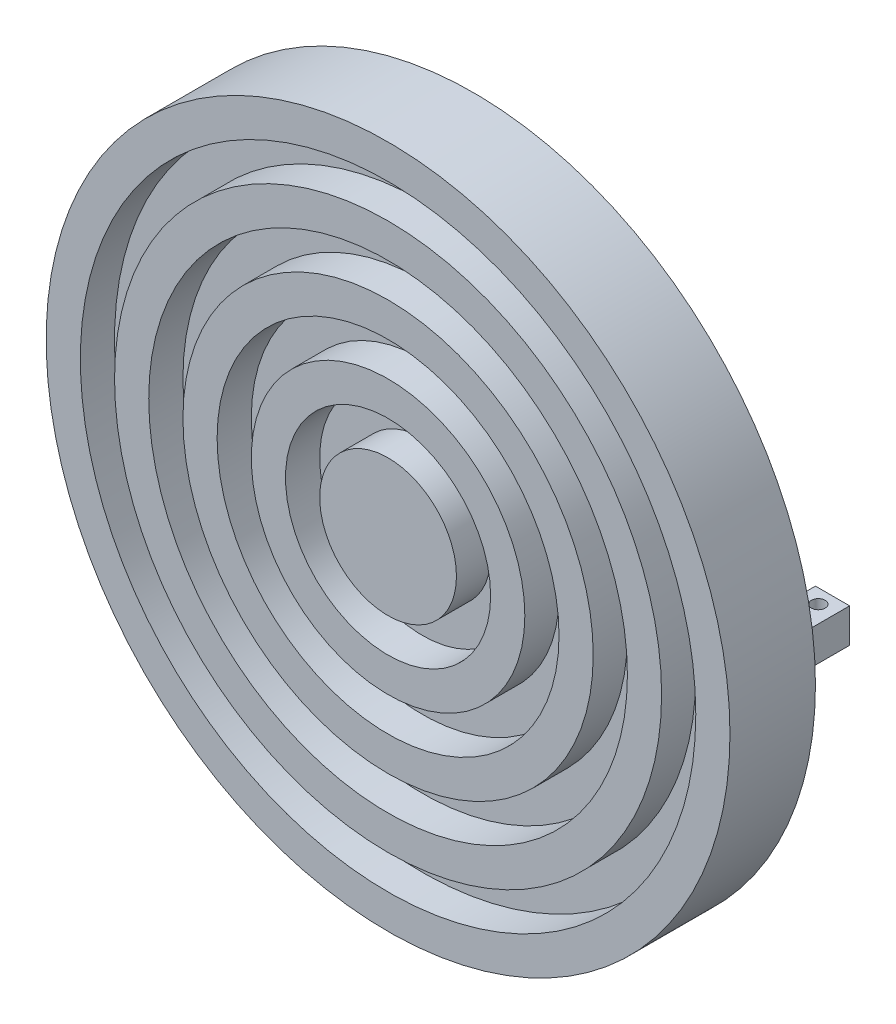
SolidWorks part; units mm, degrees
ref_plane "Front Plane" through (0, 0, 0) normal (1, 0, 0) x (0, 1, 0)
ref_plane "Top Plane" through (0, 0, 0) normal (0, 0, 1) x (0, 1, 0)
ref_plane "Right Plane" through (0, 0, 0) normal (0, 1, 0) x (-1, 0, 0)
sketch "Sketch1" plane through (0, 0, 0) normal (0, 0, 1) x (0, 1, 0)
  circle A0 centre (0, 0) radius 10
  dimension "D1" = 20
extrude "Boss-Extrude1" add sketch "Sketch1" along normal blind 2.5 contours A0
sketch "Sketch5" plane through (0, 0, 0) normal (0, 1, 0) x (-1, 0, 0)
  line L0 (0, 2.5) -> (0, -4.1897) construction
  line L1 (10, 2.5) -> (-10, 2.5) construction
  line L2 (-4, 2.5) -> (-4, 1.5)
  line L3 (-2, 2.5) -> (-3, 2.5)
  line L4 (-2, 2.5) -> (-2, 1.5)
  line L5 (-2, 1.5) -> (-3, 1.5)
  line L6 (-3, 2.5) -> (-3, 1.5)
  line L7 (-4, 2.5) -> (-5, 2.5)
  line L8 (-5, 2.5) -> (-5, 1.5)
  line L9 (-4, 1.5) -> (-5, 1.5)
  line L10 (-6, 2.5) -> (-6, 1.5)
  line L11 (-6, 2.5) -> (-7, 2.5)
  line L12 (-7, 2.5) -> (-7, 1.5)
  line L13 (-6, 1.5) -> (-7, 1.5)
  line L14 (-8, 2.5) -> (-8, 1.5)
  line L15 (-8, 2.5) -> (-9, 2.5)
  line L16 (-9, 2.5) -> (-9, 1.5)
  line L17 (-8, 1.5) -> (-9, 1.5)
  dimension "D1" = 2
  dimension "D2" = 3
  dimension "D3" = 1
  dimension "D4" = 4
revolve "Cut-Revolve1" cut sketch "Sketch5" angle 360 about L0
sketch "Sketch6" plane through (0, 0, 0) normal (0, 1, 0) x (-1, 0, 0)
  line L0 (0, -0.1135) -> (0, -3.7394) construction
  line L1 (-10, 0) -> (10, 0) construction
  line L2 (-2, 0) -> (-3, 0)
  line L3 (-2, 0) -> (-2, -2)
  line L4 (-2, -2) -> (-3, -2)
  line L5 (-3, 0) -> (-3, -2)
  line L6 (-4, 0) -> (-4, -2)
  line L7 (-4, 0) -> (-5, 0)
  line L8 (-5, 0) -> (-5, -2)
  line L9 (-4, -2) -> (-5, -2)
  line L10 (-6, 0) -> (-6, -2)
  line L11 (-6, 0) -> (-7, 0)
  line L12 (-7, 0) -> (-7, -2)
  line L13 (-6, -2) -> (-7, -2)
  line L14 (-8, 0) -> (-8, -2)
  line L15 (-8, 0) -> (-9, 0)
  line L16 (-9, 0) -> (-9, -2)
  line L17 (-8, -2) -> (-9, -2)
  dimension "D1" = 4
  dimension "D2" = 1
  dimension "D3" = 2
  dimension "D4" = 4
extrude "Boss-Extrude2" add sketch "Sketch6" along normal mid plane 1
sketch "Sketch7" plane through (0, 0, 0) normal (0, 1, 0) x (-1, 0, 0)
  circle A0 centre (-8.5, -1.5834) radius 0.2
  circle A1 centre (-6.5, -1.5834) radius 0.2
  circle A2 centre (-4.5, -1.5834) radius 0.2
  circle A3 centre (-2.5, -1.5834) radius 0.2
  dimension "D1" = 0.4
  dimension "D2" = 4
extrude "Cut-Extrude1" cut sketch "Sketch7" against normal mid plane 3
